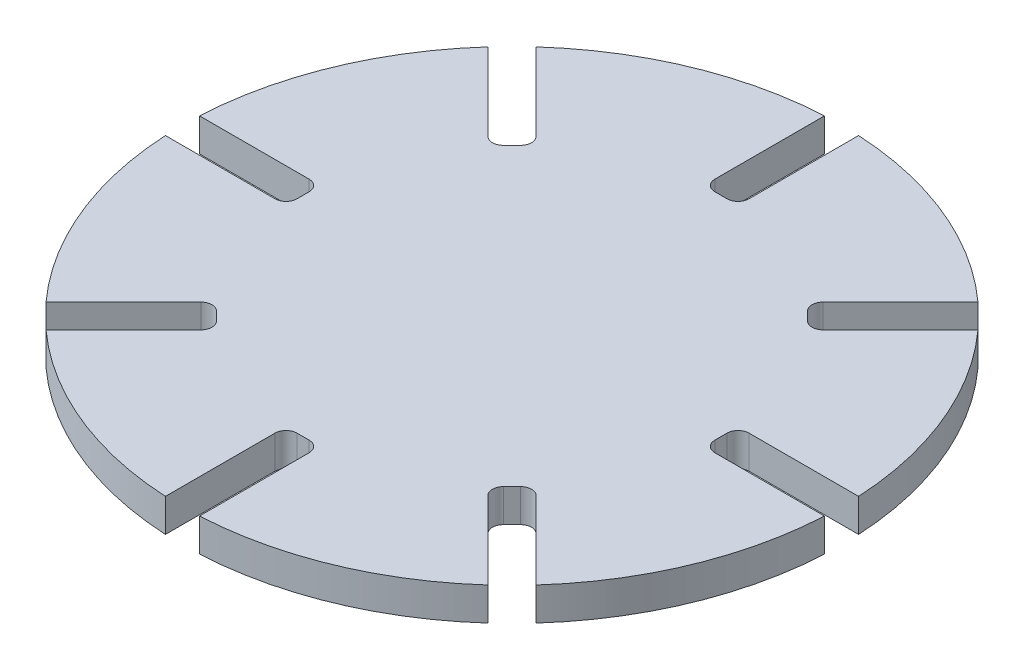
SolidWorks part; units mm, degrees
ref_plane "前视基准面" through (0, 0, 0) normal (0, 0, 1) x (1, 0, 0)
ref_plane "上视基准面" through (0, 0, 0) normal (0, 1, 0) x (1, 0, 0)
ref_plane "右视基准面" through (0, 0, 0) normal (1, 0, 0) x (0, 0, -1)
sketch "草图2" plane through (0, 0, 0) normal (0, 1, 0) x (1, 0, 0)
  line L0 (0, 0) -> (88.2448, 0) construction
  circle A0 centre (0, 0) radius 60
  dimension "D1" = 120
extrude "凸台-拉伸1" add sketch "草图2" along normal blind 6 contours A0
sketch "草图3" plane through (0, 6, 0) normal (0, 1, 0) x (1, 0, 0)
  line L0 (0, 0) -> (105.9564, 0) construction
  line L2 (38, 3.1) -> (98, 3.1)
  line L3 (38, 3.1) -> (38, -3.1)
  line L4 (38, -3.1) -> (98, -3.1)
  line L5 (98, 3.1) -> (98, -3.1)
  line L33 (24.678, -29.0621) -> (67.1044, -71.4885)
  line L34 (29.0621, -24.678) -> (24.678, -29.0621)
  line L35 (29.0621, -24.678) -> (71.4885, -67.1044)
  line L36 (71.4885, -67.1044) -> (67.1044, -71.4885)
  line L37 (-3.1, -38) -> (-3.1, -98)
  line L38 (3.1, -38) -> (-3.1, -38)
  line L39 (3.1, -38) -> (3.1, -98)
  line L40 (3.1, -98) -> (-3.1, -98)
  line L41 (-29.0621, -24.678) -> (-71.4885, -67.1044)
  line L42 (-24.678, -29.0621) -> (-29.0621, -24.678)
  line L43 (-24.678, -29.0621) -> (-67.1044, -71.4885)
  line L44 (-67.1044, -71.4885) -> (-71.4885, -67.1044)
  line L45 (-38, 3.1) -> (-98, 3.1)
  line L46 (-38, -3.1) -> (-38, 3.1)
  line L47 (-38, -3.1) -> (-98, -3.1)
  line L48 (-98, -3.1) -> (-98, 3.1)
  line L49 (-24.678, 29.0621) -> (-67.1044, 71.4885)
  line L50 (-29.0621, 24.678) -> (-24.678, 29.0621)
  line L51 (-29.0621, 24.678) -> (-71.4885, 67.1044)
  line L52 (-71.4885, 67.1044) -> (-67.1044, 71.4885)
  line L53 (3.1, 38) -> (3.1, 98)
  line L54 (-3.1, 38) -> (3.1, 38)
  line L55 (-3.1, 38) -> (-3.1, 98)
  line L56 (-3.1, 98) -> (3.1, 98)
  line L57 (29.0621, 24.678) -> (71.4885, 67.1044)
  line L58 (24.678, 29.0621) -> (29.0621, 24.678)
  line L59 (24.678, 29.0621) -> (67.1044, 71.4885)
  line L60 (67.1044, 71.4885) -> (71.4885, 67.1044)
  point P37 (0, 6)
  point P39 (0, 0)
  dimension "D1" = 6.2
  dimension "D2" = 38
  dimension "D3" = 60
extrude "切除-拉伸1" cut sketch "草图3" against normal blind 6
fillet "圆角1" radius 2 16 edges at (38, 3, 3.1) (38, 3, -3.1) (24.678, 3, 29.0621) (29.0621, 3, 24.678) (-3.1, 3, 38) (3.1, 3, 38) (-29.0621, 3, 24.678) (-24.678, 3, 29.0621) (-38, 3, 3.1) (-38, 3, -3.1) (-29.0621, 3, -24.678) (-24.678, 3, -29.0621) (-3.1, 3, -38) (3.1, 3, -38) (24.678, 3, -29.0621) (29.0621, 3, -24.678)
